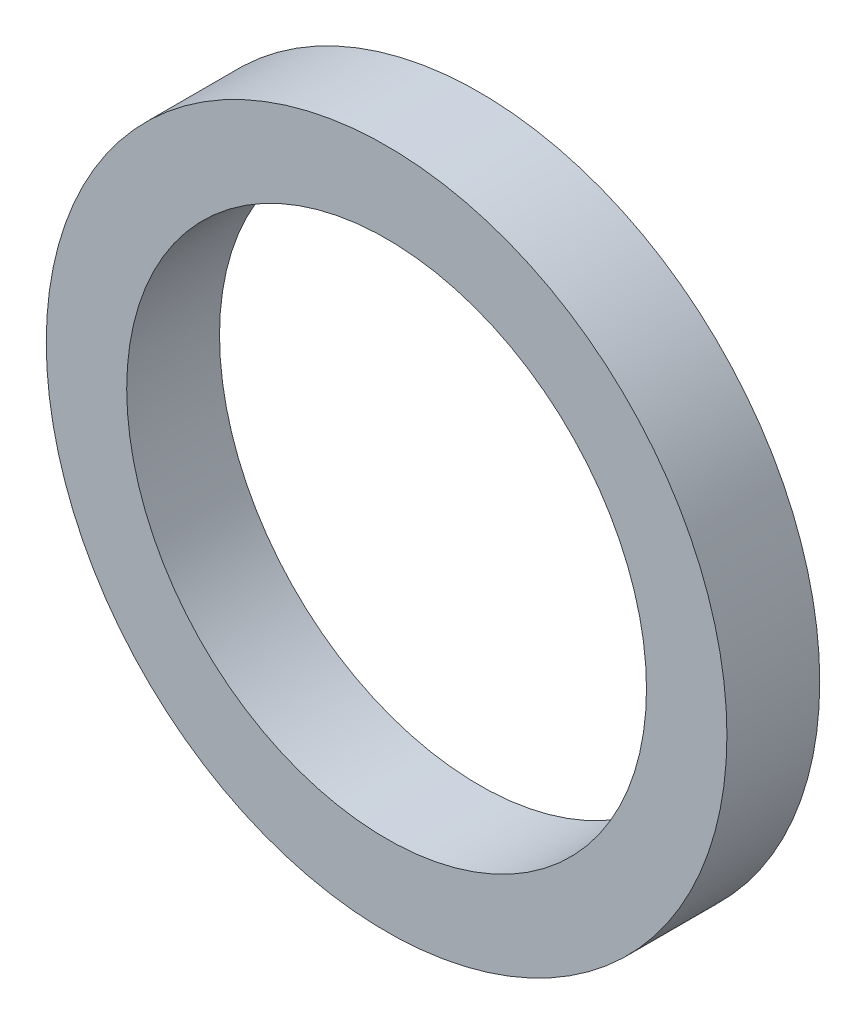
SolidWorks part; units mm, degrees
ref_plane "Front Plane" through (0, 0, 0) normal (0, 0, 1) x (1, 0, 0)
ref_plane "Top Plane" through (0, 0, 0) normal (0, 1, 0) x (1, 0, 0)
ref_plane "Right Plane" through (0, 0, 0) normal (1, 0, 0) x (0, 0, -1)
sketch "Sketch1" plane through (0, 0, 0) normal (0, 0, 1) x (1, 0, 0)
  circle A0 centre (0, 0) radius 5.5
extrude "Boss-Extrude1" add sketch "Sketch1" along normal blind 1.5 from offset 10.5
sketch "Sketch2" plane through (0, 0, 0) normal (0, 0, 1) x (1, 0, 0)
  circle A0 centre (0, 0) radius 4.2
extrude "Cut-Extrude1" cut sketch "Sketch2" against normal through all and the other way through all
